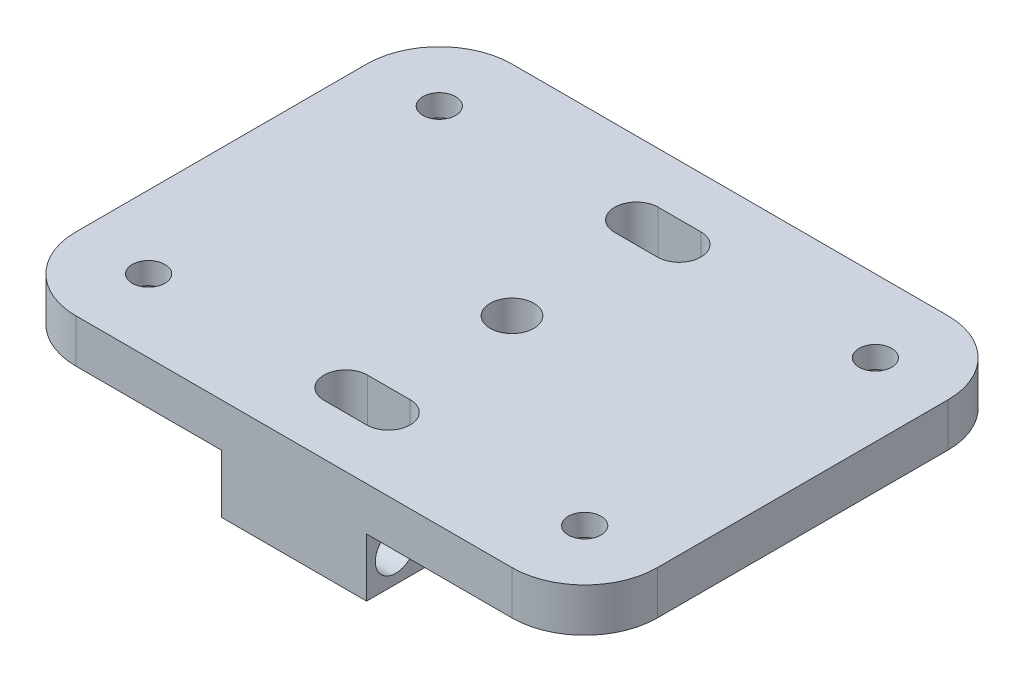
SolidWorks part; units mm, degrees
ref_plane "Plan de face" through (0, 0, 0) normal (0, 0, 1) x (1, 0, 0)
ref_plane "Plan de dessus" through (0, 0, 0) normal (0, 1, 0) x (1, 0, 0)
ref_plane "Plan de droite" through (0, 0, 0) normal (1, 0, 0) x (0, 0, -1)
sketch "Esquisse1" plane through (0, 0, 0) normal (0, 1, 0) x (1, 0, 0)
  line L0 (30, 20) -> (-35.7533, -23.8355) construction
  line L1 (-30, 30) -> (30, 30)
  line L2 (-40, 20) -> (-40, -20)
  line L3 (-30, -30) -> (30, -30)
  line L4 (40, 20) -> (40, -20)
  line L5 (-29.1047, 30) -> (-9.1047, 30)
  line L7 (-29.1047, -30) -> (-9.1047, -30)
  line L9 (-30, 20) -> (30, -20) construction
  arc A0 (-30, 30) -> (-40, 20) centre (-30, 20) ccw
  arc A1 (-40, -20) -> (-30, -30) centre (-30, -20) ccw
  arc A2 (30, -30) -> (40, -20) centre (30, -20) ccw
  arc A3 (30, 30) -> (40, 20) centre (30, 20) cw
  circle A4 centre (-30, 20) radius 2.25
  circle A5 centre (30, 20) radius 2.25
  circle A6 centre (-30, -20) radius 2.25
  circle A7 centre (30, -20) radius 2.25
  circle A8 centre (0, 0) radius 3
  point P7 (-40, 30)
  point P12 (40, -30)
  point P15 (40, 30)
  dimension "D3" = 10
  dimension "D4" = 6
  dimension "D5" = 4.5
  dimension "D1" = 80
  dimension "D2" = 60
extrude "Boss.-Extru.3" add sketch "Esquisse1" along normal blind 6 contours A3 L1 A0 L2 A1 L3 A2 L4 A8 A7 A6 A5 A4
sketch "Esquisse2" plane through (0, 0, 0) normal (0, -1, 0) x (1, 0, 0)
  line L0 (-30, 30) -> (30, 30) construction
  line L1 (-10, 30) -> (10, 30)
  line L2 (-10, 30) -> (-10, -30)
  line L3 (-10, -30) -> (10, -30)
  line L4 (10, 30) -> (10, -30)
  line L5 (-30, -30) -> (30, -30) construction
  line L6 (-40, -20) -> (-40, 20) construction
  circle A4 centre (0, 0) radius 3 construction
  circle A5 centre (0, 0) radius 3
  dimension "D1" = 20
  dimension "D2" = 30
extrude "Boss.-Extru.4" add sketch "Esquisse2" along normal blind 8
sketch "Esquisse3" plane through (0, 0, 0) normal (0, -1, 0) x (1, 0, 0)
  line L0 (-30, 20) -> (30, -20) construction
  line L1 (-30, -20) -> (30, 20) construction
  circle A0 centre (-30, 20) radius 4
  circle A1 centre (-30, -20) radius 4
  circle A2 centre (30, 20) radius 4
  circle A3 centre (30, -20) radius 4
extrude "Enlèv. mat.-Extru.2" cut sketch "Esquisse3" against normal blind 3
sketch "Esquisse7" plane through (-10, 0, 0) normal (-1, 0, 0) x (0, 0, 1)
  line L0 (26, -3.8774) -> (-26, -3.8774) construction
  line L1 (30, -8) -> (30, 0) construction
  line L2 (30, 0) -> (-30, 0) construction
  line L3 (-30, -8) -> (-30, 0) construction
  line L4 (30, -8) -> (-30, -8) construction
  circle A2 centre (26, -3.8774) radius 2.8
  circle A3 centre (-26, -3.8774) radius 2.8
  dimension "D1" = 5.6
  dimension "D2" = 4
  dimension "D3" = 4.1226
  dimension "D4" = 4
extrude "Enlèv. mat.-Extru.8" cut sketch "Esquisse7" against normal blind 8.1
sketch "Esquisse8" plane through (0, -8, 0) normal (0, -1, 0) x (1, 0, 0)
  line L0 (-2.8795, 20) -> (3, 20) construction
  line L1 (-2.8795, 23) -> (3, 23)
  line L2 (-2.8795, 17) -> (3, 17)
  line L3 (-2.8795, -20) -> (3, -20) construction
  line L4 (-2.8795, -17) -> (3, -17)
  line L5 (-2.8795, -23) -> (3, -23)
  line L6 (10, 30) -> (-10, 30) construction
  line L7 (-10, -30) -> (10, -30) construction
  line L9 (10, -30) -> (10, 30) construction
  line L10 (-10, 30) -> (-10, -30) construction
  arc A0 (-2.8795, 23) -> (-2.8795, 17) centre (-2.8795, 20) ccw
  arc A1 (3, 17) -> (3, 23) centre (3, 20) ccw
  arc A2 (-2.8795, -17) -> (-2.8795, -23) centre (-2.8795, -20) ccw
  arc A3 (3, -23) -> (3, -17) centre (3, -20) ccw
  point P2 (0.0602, 20)
  point P7 (0.0602, -20)
  dimension "D1" = 10
  dimension "D3" = 7
  dimension "D4" = 7
  dimension "D6" = 7.1205
  dimension "D2" = 10
  dimension "D5" = 7
extrude "Enlèv. mat.-Extru.9" cut sketch "Esquisse8" against normal through all
sketch "Esquisse9" plane through (10, 0, 0) normal (1, 0, 0) x (0, 0, -1)
  line L0 (-30, -8) -> (-30, 0) construction
  line L1 (30, -8) -> (30, 0) construction
  line L3 (-26, -3.88) -> (26, -3.88) construction
  line L5 (30, -8) -> (-30, -8) construction
  circle A0 centre (-26, -3.88) radius 2.8
  circle A1 centre (26, -3.88) radius 2.8
  dimension "D1" = 5.6
  dimension "D2" = 4
  dimension "D3" = 4
  dimension "D4" = 4.12
  dimension "D5" = 4.12
extrude "Enlèv. mat.-Extru.10" cut sketch "Esquisse9" against normal blind 8.1
